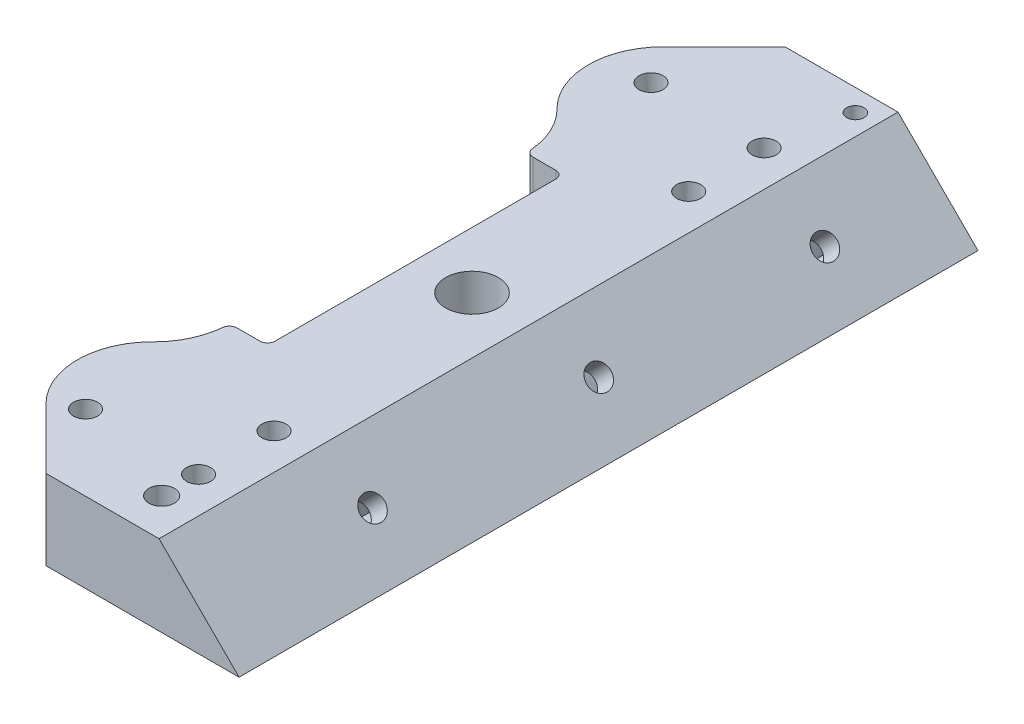
SolidWorks part; units mm, degrees
ref_plane "前视基准面" through (0, 0, 0) normal (0, 0, 1) x (1, 0, 0)
ref_plane "上视基准面" through (0, 0, 0) normal (0, 1, 0) x (1, 0, 0)
ref_plane "右视基准面" through (0, 0, 0) normal (1, 0, 0) x (0, 0, -1)
sketch "Sketch1" plane through (0, 0, 0) normal (0, 0, 1) x (1, 0, 0)
  line L0 (0, 0) -> (30, 0)
  line L1 (30, 0) -> (40.6066, -10.6066)
  line L2 (0, 0) -> (0, -10.6066)
  line L4 (0, -10.6066) -> (40.6066, -10.6066)
  dimension "D1" = 135
  dimension "D2" = 15
  dimension "D3" = 30
extrude "Extrude1" add sketch "Sketch1" along normal blind 98 contours L2 L4 L1 L0
sketch "Sketch2" plane through (15, 15, 0) normal (0.7071, 0.7071, 0) x (0, 0, -1)
  line L0 (-98, -28.7132) -> (-75, -28.7132) construction
  line L1 (-98, -21.2132) -> (-98, -36.2132) construction
  line L2 (0, -28.7132) -> (-15, -28.7132) construction
  line L3 (0, -21.2132) -> (0, -36.2132) construction
  line L4 (-75, -28.7132) -> (-45, -28.7132) construction
  circle A0 centre (-75, -28.7132) radius 1.6
  circle A1 centre (-45, -28.7132) radius 1.6
  circle A2 centre (-15, -28.7132) radius 1.6
  dimension "D1" = 3.2
  dimension "D3" = 3.2
  dimension "D4" = 30
  dimension "D5" = 3.2
  dimension "D6" = 53
  dimension "D2" = 30
extrude "Extrude2" cut sketch "Sketch2" against normal blind 98
sketch "Sketch3" plane through (0, 0, 0) normal (0, 1, 0) x (1, 0, 0)
  line L0 (30, -98) -> (30, 0) construction
  line L1 (0, -49) -> (45.4968, -49) construction
  line L2 (25.24, -11.4) -> (25.24, -13) construction
  line L3 (25.24, -13) -> (25.24, -33.4) construction
  line L4 (25.24, -35) -> (25.24, -57.65) construction
  line L5 (25.24, -59.25) -> (25.24, -88) construction
  line L6 (0, -98) -> (0, 0) construction
  line L9 (0, -98) -> (30, -98) construction
  circle A0 centre (25.24, -13) radius 1.6
  circle A3 centre (25.24, -88) radius 1.6
  dimension "D5" = 3.2
  dimension "D8" = 3.2
  dimension "D9" = 10
  dimension "D1" = 4.76
  dimension "D2" = 22
  dimension "D3" = 24.25
  dimension "D4" = 28.75
extrude "Extrude3" cut sketch "Sketch3" against normal through all
sketch "Sketch4" plane through (0, -10.6066, 0) normal (0, -1, 0) x (-1, 0, 0)
  line L0 (0, 0) -> (0, -35) construction
  line L2 (0, -98) -> (0, 0) construction
sketch "Sketch5" plane through (0, 0, 0) normal (0, 1, 0) x (1, 0, 0)
  line L0 (0, 0) -> (0, -35) construction
  line L1 (0, 0) -> (0, -35) construction
  line L10 (-6, -44.6699) -> (10, -44.6699)
  line L11 (-6, -44.6699) -> (-6, -25.3301)
  line L12 (-6, -25.3301) -> (10, -25.3301)
  line L13 (10, -44.6699) -> (10, -25.3301)
  line L14 (-6, -44.6699) -> (0, -35) construction
  line L15 (-6, -25.3301) -> (0, -35) construction
  dimension "D1" = 35
  dimension "D2" = 10
  dimension "D3" = 16
extrude "Extrude4" cut sketch "Sketch5" against normal blind 14
ref_plane "Plane1" through (12.8787, 12.8787, 0) normal (0.7071, 0.7071, 0) x (0, 0, -1)
sketch "Sketch6" plane through (12.8787, 12.8787, 0) normal (0.7071, 0.7071, 0) x (0, 0, -1)
  line L1 (-18.2939, -28.1104) -> (-17.169, -31.2644)
  line L2 (-17.169, -31.2644) -> (-13.8751, -31.8672)
  line L3 (-13.8751, -31.8672) -> (-11.7061, -29.316)
  line L4 (-11.7061, -29.316) -> (-12.831, -26.162)
  line L5 (-12.831, -26.162) -> (-16.1249, -25.5592)
  line L6 (-16.1249, -25.5592) -> (-18.2939, -28.1104)
  line L7 (-48.0889, -27.4202) -> (-47.6642, -30.7418)
  line L8 (-47.6642, -30.7418) -> (-44.5753, -32.0348)
  line L9 (-44.5753, -32.0348) -> (-41.9111, -30.0062)
  line L10 (-41.9111, -30.0062) -> (-42.3358, -26.6846)
  line L11 (-42.3358, -26.6846) -> (-45.4247, -25.3916)
  line L12 (-45.4247, -25.3916) -> (-48.0889, -27.4202)
  line L13 (-78.3407, -28.4829) -> (-76.8698, -31.4912)
  line L14 (-76.8698, -31.4912) -> (-73.5291, -31.7215)
  line L15 (-73.5291, -31.7215) -> (-71.6593, -28.9436)
  line L16 (-71.6593, -28.9436) -> (-73.1302, -25.9352)
  line L17 (-73.1302, -25.9352) -> (-76.4709, -25.7049)
  line L18 (-76.4709, -25.7049) -> (-78.3407, -28.4829)
  circle A0 centre (-15, -28.7132) radius 2.9 construction
  circle A1 centre (-45, -28.7132) radius 2.9 construction
  circle A2 centre (-75, -28.7132) radius 2.9 construction
  dimension "D1" = 5.8
  dimension "D2" = 5.8
  dimension "D3" = 5.8
extrude "Extrude5" cut sketch "Sketch6" against normal blind 14
ref_plane "Plane2" through (0, 0, 49) normal (0, 0, -1) x (-1, 0, 0)
mirror "Mirror1" about plane through (0, 0, 49) normal (0, 0, -1) of "Extrude4"
chamfer "Chamfer1" distance 15 angle 45 2 edges at (0, -5.3033, 98) (0, -5.3033, 0)
sketch "Sketch8" plane through (0, 0, 0) normal (0, 1, 0) x (1, 0, 0)
  line L1 (10, -53.3301) -> (-3.8736, -53.3301)
  line L2 (10, -53.3301) -> (10, -41.0874)
  line L3 (10, -41.0874) -> (-3.8736, -41.0874)
  line L4 (-3.8736, -53.3301) -> (-3.8736, -41.0874)
extrude "Extrude6" cut sketch "Sketch8" against normal blind 24
sketch "Sketch9" plane through (0, 0, 0) normal (0, 0, -1) x (-1, 0, 0)
  line L0 (0, 0) -> (-15, -10.6066)
  line L1 (-15, -10.6066) -> (0, -10.6066)
  line L2 (0, -10.6066) -> (0, 0)
sketch "草图1" plane through (0, 0, 0) normal (0, 1, 0) x (1, 0, 0)
  line L0 (25.24, -13) -> (10.24, -13) construction
  line L3 (25.24, -88) -> (10.24, -88) construction
  circle A0 centre (25.24, -13) radius 1.6
  circle A1 centre (10.24, -13) radius 1.6
  circle A4 centre (10.24, -88) radius 1.6
  dimension "D1" = 3.2
  dimension "D4" = 3.2
  dimension "D5" = 15
  dimension "D6" = 15
extrude "切除-拉伸1" cut sketch "草图1" against normal blind 18
sketch "草图2" plane through (0, 0, 0) normal (0, 1, 0) x (1, 0, 0)
  line L0 (10, -72.6699) -> (0, -83)
  line L1 (0, -83) -> (0, -72.6699)
  line L2 (0, -72.6699) -> (10, -72.6699)
  line L3 (10, -25.3301) -> (0, -15)
  line L4 (0, -15) -> (0, -25.3301)
  line L5 (0, -25.3301) -> (10, -25.3301)
extrude "切除-拉伸2" cut sketch "草图2" against normal blind 21
fillet "圆角1" radius 10 4 edges at (0, -5.3033, 83) (10, -5.3033, 72.6699) (10, -5.3033, 25.3301) (0, -5.3033, 15)
sketch "草图3" plane through (0, 0, 0) normal (0, 1, 0) x (1, 0, 0)
  line L0 (10, -29.3774) -> (15, -29.3774)
  line L1 (10, -68.6226) -> (15, -68.6226)
  line L2 (15, -68.6226) -> (15, -29.3774)
  line L3 (10, -29.3774) -> (10, -68.6226)
  dimension "D1" = 5
extrude "切除-拉伸3" cut sketch "草图3" against normal blind 36
fillet "圆角2" radius 1 4 edges at (10, -5.3033, 29.3774) (10, -5.3033, 68.6226) (15, -5.3033, 68.6226) (15, -5.3033, 29.3774)
sketch "草图4" plane through (0, 0, 0) normal (0, 1, 0) x (1, 0, 0)
  line L0 (30, -49) -> (15, -49) construction
  line L1 (30, -98) -> (30, 0) construction
  line L2 (15, -67.6226) -> (15, -30.3774) construction
  line L4 (24.463, -49) -> (23.4815, -47.3)
  line L5 (23.4815, -47.3) -> (21.5185, -47.3)
  line L6 (21.5185, -47.3) -> (20.537, -49)
  line L7 (20.537, -49) -> (21.5185, -50.7)
  line L8 (21.5185, -50.7) -> (23.4815, -50.7)
  line L9 (23.4815, -50.7) -> (24.463, -49)
  circle A0 centre (22.5, -49) radius 1.7 construction
  dimension "D1" = 3.4
extrude "切除-拉伸4" cut sketch "草图4" against normal blind 36
sketch "草图5" plane through (0, 0, 0) normal (0, 1, 0) x (1, 0, 0)
  line L0 (5.8336, -49) -> (-5.8336, -49) construction
  circle A0 centre (22.5, -49) radius 3.5
  dimension "D1" = 7
extrude "切除-拉伸5" cut sketch "草图5" against normal blind 27
sketch "草图6" plane through (0, 0, 0) normal (0, 1, 0) x (1, 0, 0)
  line L0 (27.24, -4.05) -> (27.24, 0) construction
  line L1 (15, 0) -> (30, 0) construction
  line L2 (30, -98) -> (30, 0) construction
  circle A0 centre (27.24, -2.9) radius 1.15
  dimension "D1" = 2.9
  dimension "D2" = 2.3
  dimension "D3" = 2.76
extrude "切除-拉伸6" cut sketch "草图6" against normal blind 17
sketch "草图7" plane through (0, 0, 0) normal (0, 1, 0) x (1, 0, 0)
  line L0 (25.24, -88) -> (25.24, -78) construction
  circle A0 centre (25.24, -78) radius 1.6
  dimension "D1" = 3.2
extrude "切除-拉伸7" cut sketch "草图7" against normal blind 23
sketch "草图8" plane through (0, -10.6066, 0) normal (0, -1, 0) x (-1, 0, 0)
  line L0 (-25.24, -13) -> (-25.24, -23) construction
  circle A0 centre (-25.24, -23) radius 1.6
  dimension "D1" = 3.2
extrude "切除-拉伸8" cut sketch "草图8" against normal blind 19
sketch "草图9" plane through (0, 0, 0) normal (0, 1, 0) x (1, 0, 0)
  line L0 (25.24, -89.6) -> (25.24, -94.7437) construction
  line L1 (15, -98) -> (30, -98) construction
  circle A0 centre (25.24, -92.9) radius 1.7
  circle A3 centre (25.24, -88) radius 1.6 construction
  dimension "D1" = 3.4
  dimension "D2" = 5.1
extrude "切除-拉伸9" cut sketch "草图9" against normal blind 15
